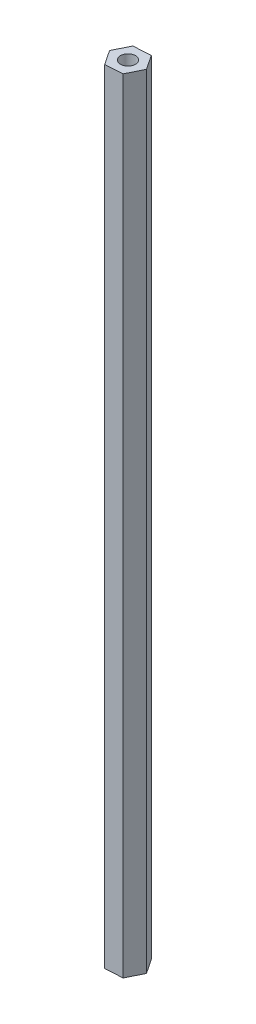
SolidWorks part; units mm, degrees
ref_plane "前视基准面" through (0, 0, 0) normal (0, 0, 1) x (1, 0, 0)
ref_plane "上视基准面" through (0, 0, 0) normal (0, 1, 0) x (1, 0, 0)
ref_plane "右视基准面" through (0, 0, 0) normal (1, 0, 0) x (0, 0, -1)
sketch "草图1" plane through (0, 0, 0) normal (0, 1, 0) x (1, 0, 0)
  line L1 (1.9215, -2.8823) -> (3.4569, 0.2229)
  line L2 (3.4569, 0.2229) -> (1.5354, 3.1053)
  line L3 (1.5354, 3.1053) -> (-1.9215, 2.8823)
  line L4 (-1.9215, 2.8823) -> (-3.4569, -0.2229)
  line L5 (-3.4569, -0.2229) -> (-1.5354, -3.1053)
  line L6 (-1.5354, -3.1053) -> (1.9215, -2.8823)
  circle A0 centre (0, 0) radius 3 construction
  circle A1 centre (0, 0) radius 1.5
  dimension "D1" = 6
  dimension "D2" = 3
extrude "凸台-拉伸1" add sketch "草图1" along normal blind 156
